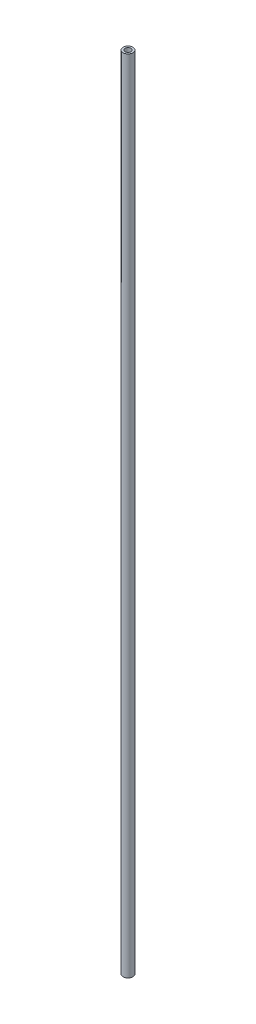
SolidWorks part; units mm, degrees
material "Zoltek Panex 33"
ref_plane "Front Plane" through (0, 0, 0) normal (0, 0, 1) x (1, 0, 0)
ref_plane "Top Plane" through (0, 0, 0) normal (0, 1, 0) x (1, 0, 0)
ref_plane "Right Plane" through (0, 0, 0) normal (1, 0, 0) x (0, 0, -1)
sketch "Sketch2" plane through (0, 0, 0) normal (0, 1, 0) x (1, 0, 0)
  circle A0 centre (0, 0) radius 2.5
  circle A1 centre (0, 0) radius 1.5
  dimension "D1" = 5
  dimension "D2" = 3
extrude "Boss-Extrude1" add sketch "Sketch2" along normal mid plane 410
